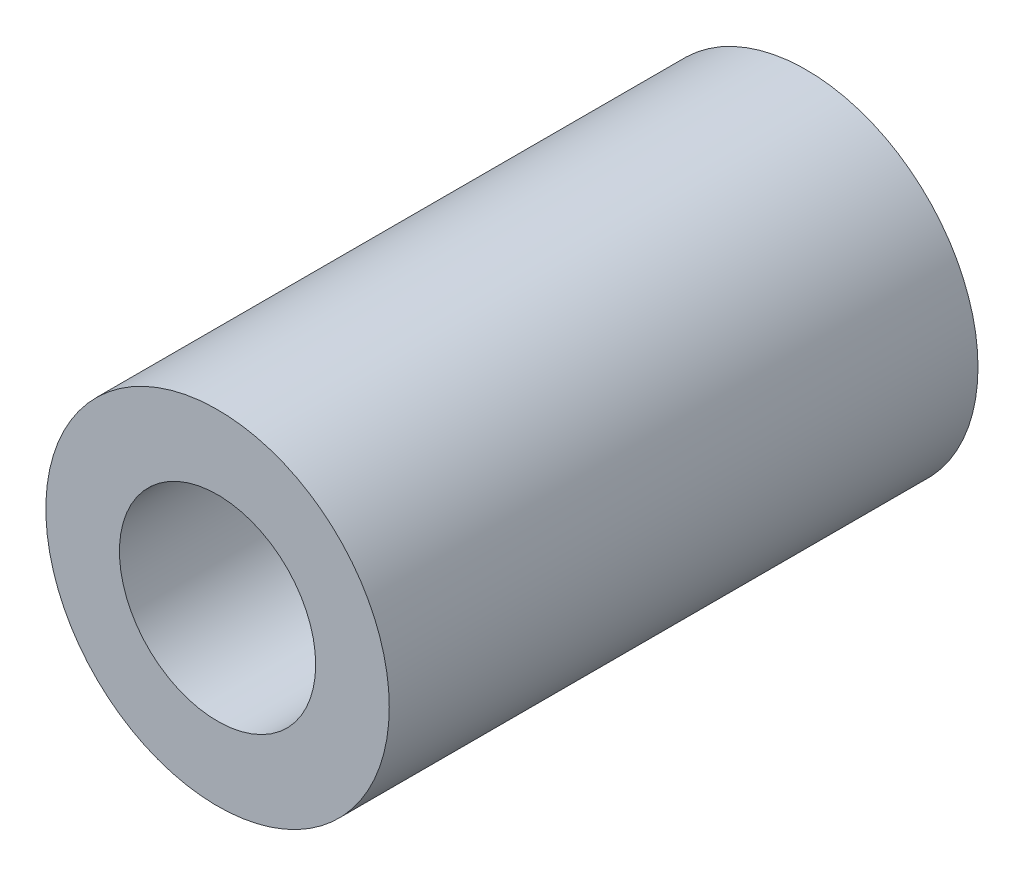
SolidWorks part; units mm, degrees
ref_plane "Plan1" through (0, 0, 0) normal (0, 0, 1) x (1, 0, 0)
ref_plane "Plan2" through (0, 0, 0) normal (0, 1, 0) x (1, 0, 0)
ref_plane "Plan3" through (0, 0, 0) normal (1, 0, 0) x (0, 0, -1)
sketch "Esquisse1" plane through (0, 0, 0) normal (0, 0, 1) x (1, 0, 0)
  circle A0 centre (0, 0) radius 7
  circle A1 centre (0, 0) radius 4
  dimension "D1" = 14
  dimension "D2" = 8
extrude "Base-Extrusion" add sketch "Esquisse1" along normal blind 24
